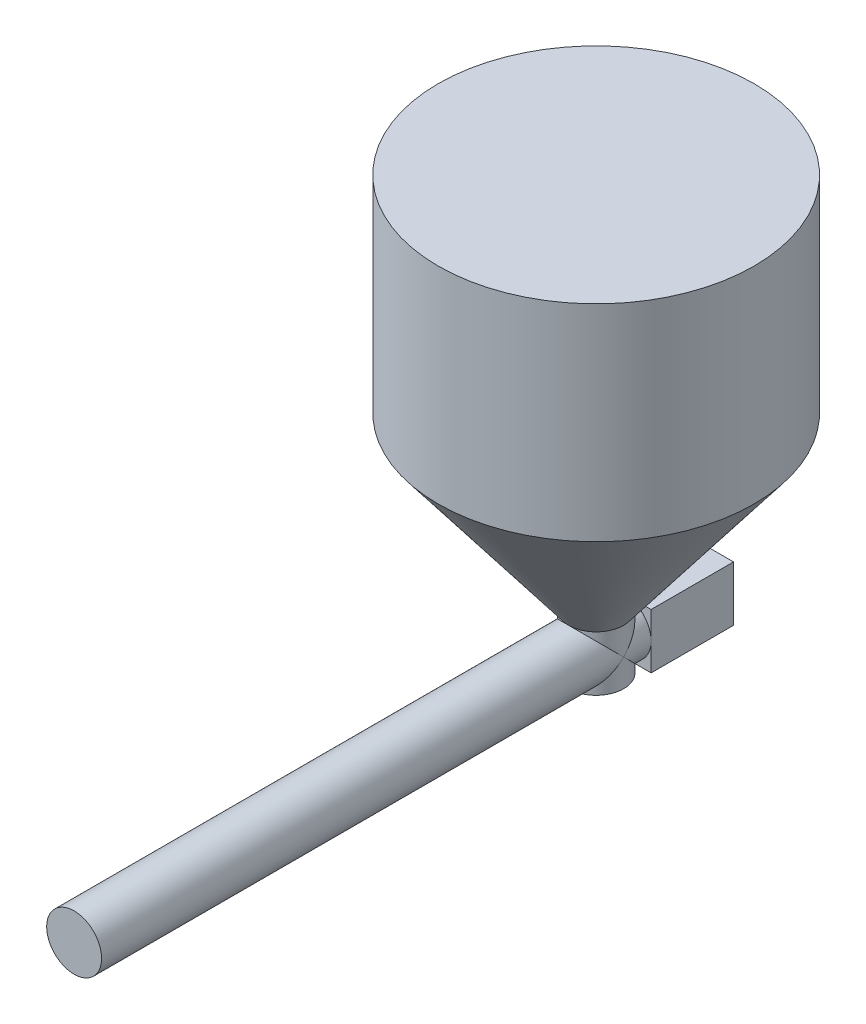
SolidWorks part; units mm, degrees
ref_plane "Alzado" through (0, 0, 0) normal (0, 0, 1) x (1, 0, 0)
ref_plane "Planta" through (0, 0, 0) normal (0, 1, 0) x (1, 0, 0)
ref_plane "Vista lateral" through (0, 0, 0) normal (1, 0, 0) x (0, 0, -1)
sketch "Croquis1" plane through (0, 0, 0) normal (0, 1, 0) x (1, 0, 0)
  circle A0 centre (0, 0) radius 115
  dimension "D1" = 230
ref_plane "Plano1" through (0, -274, 0) normal (0, 1, 0) x (1, 0, 0)
extrude "Saliente-Extruir1" add sketch "Croquis1" against normal blind 150 contours A0
sketch "Croquis2" plane through (0, -150, 0) normal (0, -1, 0) x (1, 0, 0)
  circle A1 centre (0, 0) radius 115
sketch "Croquis3" plane through (0, -274, 0) normal (0, 1, 0) x (1, 0, 0)
  circle A0 centre (0, 0) radius 20
  dimension "D1" = 40
loft "Recubrir1" add profiles "Croquis3", "Croquis2"
sketch "Croquis4" plane through (0, -274, 0) normal (0, -1, 0) x (1, 0, 0)
  circle A0 centre (0, 0) radius 20
  dimension "D1" = 40
extrude "Saliente-Extruir2" add sketch "Croquis4" along normal blind 40
ref_plane "Plano2" through (0, 0, -20) normal (0, 0, -1) x (-1, 0, 0)
sketch "Croquis5" plane through (0, 0, -20) normal (0, 0, -1) x (-1, 0, 0)
  line L0 (-20, -314) -> (20, -314) construction
  line L3 (0, -314) -> (0, -274) construction
  line L4 (126.5, -274) -> (-126.5, -274) construction
  circle A0 centre (0, -294) radius 20
  dimension "D1" = 40
extrude "Saliente-Extruir3" add sketch "Croquis5" against normal blind 400
sketch "Croquis6" plane through (0, 0, -20) normal (0, 0, -1) x (-1, 0, 0)
  line L0 (-20, -294) -> (20, -294) construction
  line L2 (-20, -274) -> (20, -274)
  line L3 (-20, -274) -> (-20, -314)
  line L4 (-20, -314) -> (20, -314)
  line L5 (20, -274) -> (20, -314)
  line L6 (-20, -274) -> (20, -314) construction
  line L7 (-20, -314) -> (20, -274) construction
  arc A0 (0, -274) -> (0, -314) centre (0, -294) ccw construction
  arc A1 (0, -314) -> (0, -274) centre (0, -294) ccw construction
  point P8 (0, -294)
  dimension "D1" = 40
  dimension "D2" = 40
extrude "Saliente-Extruir4" add sketch "Croquis6" along normal blind 60
